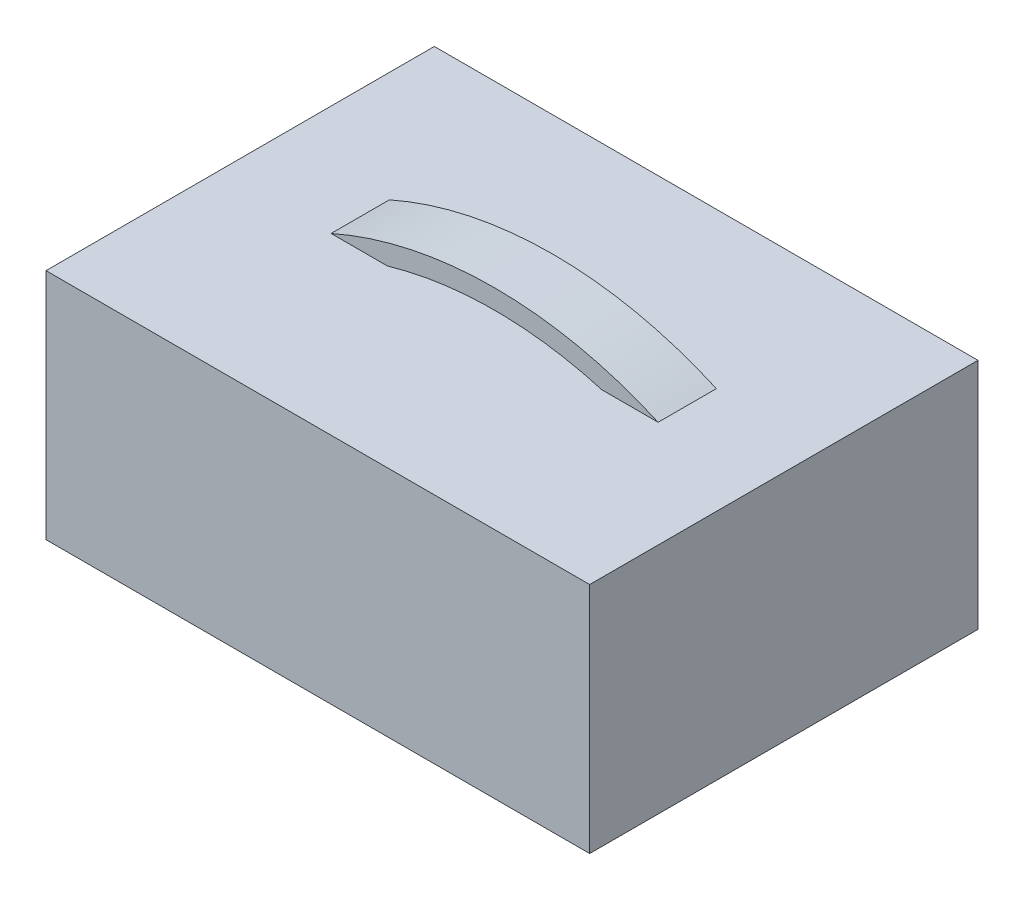
SolidWorks part; units mm, degrees
ref_plane "前视基准面" through (0, 0, 0) normal (0, 0, 1) x (1, 0, 0)
ref_plane "上视基准面" through (0, 0, 0) normal (0, 1, 0) x (1, 0, 0)
ref_plane "右视基准面" through (0, 0, 0) normal (1, 0, 0) x (0, 0, -1)
other "Configuration Table"
sketch "草图1" plane through (0, 0, 0) normal (0, 1, 0) x (1, 0, 0)
  line L1 (0, 0) -> (280, 0)
  line L2 (0, 0) -> (0, 200)
  line L3 (0, 200) -> (280, 200)
  line L4 (280, 0) -> (280, 200)
  dimension "D1" = 280
  dimension "D2" = 200
extrude "凸台-拉伸1" add sketch "草图1" along normal blind 120
sketch "草图2" plane through (0, 0, 0) normal (0, 0, 1) x (1, 0, 0)
  line L4 (0, 0) -> (280, 0)
  line L5 (280, 0) -> (280, 120)
  line L6 (280, 120) -> (0, 120)
  line L7 (0, 120) -> (0, 0)
  line L8 (0, 0) -> (280, 0) construction
  line L9 (280, 0) -> (280, 120) construction
  line L10 (280, 120) -> (0, 120) construction
  line L11 (0, 120) -> (0, 0) construction
  arc A0 (56.8405, 120) -> (225.2572, 120) centre (141.0488, -69.4172) cw
  dimension "D2" = 207.2919
  dimension "D3" = 54.7428
  dimension "D4" = 56.8405
  dimension "D1" = 0
extrude "拉伸-薄壁1" add sketch "草图2" against normal blind 30 from offset 90 thin offset against normal yes
